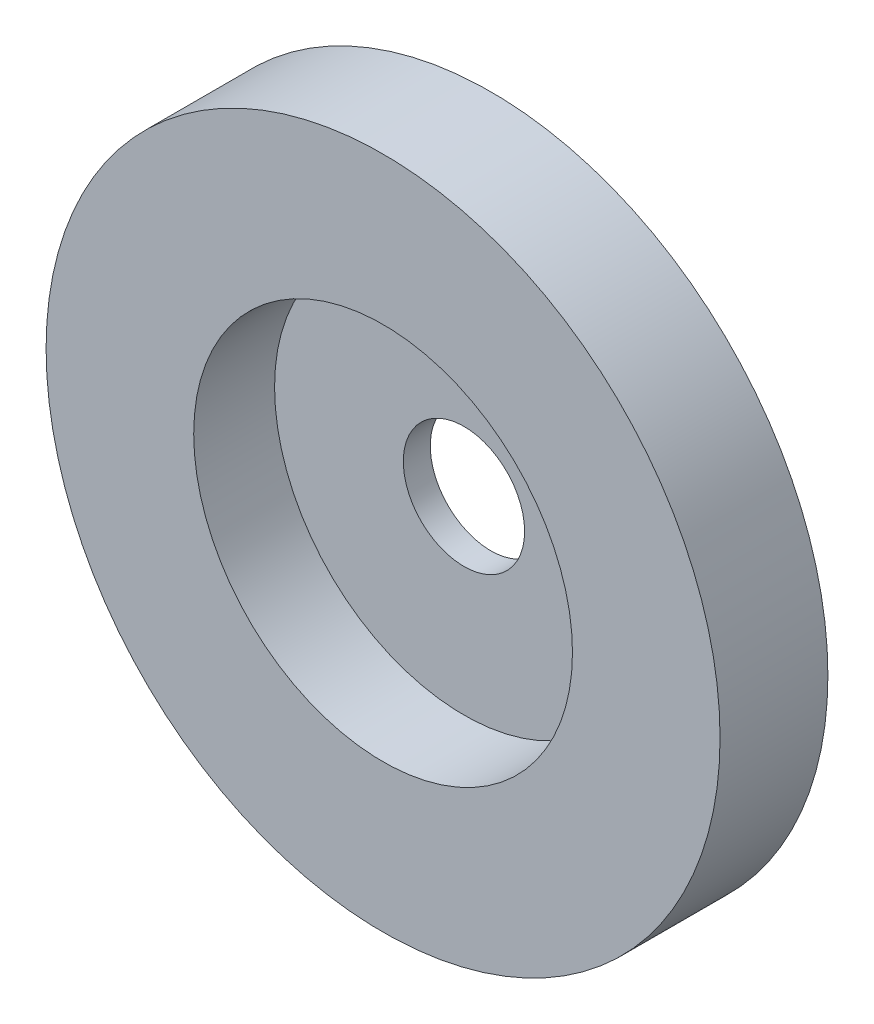
SolidWorks part; units mm, degrees
ref_plane "前基準面" through (0, 0, 0) normal (0, 0, 1) x (1, 0, 0)
ref_plane "上基準面" through (0, 0, 0) normal (0, 1, 0) x (1, 0, 0)
ref_plane "右基準面" through (0, 0, 0) normal (1, 0, 0) x (0, 0, -1)
sketch "草圖1" plane through (0, 0, 0) normal (0, 0, 1) x (1, 0, 0)
  circle A0 centre (0, 0) radius 25
extrude "填料-伸長1" add sketch "草圖1" along normal blind 8 contours A0
sketch "草圖2" plane through (0, 0, 0) normal (0, 0, 1) x (1, 0, 0)
  circle A0 centre (0, 0) radius 4.5
sketch "草圖7" plane through (0, 0, 8) normal (0, 0, 1) x (1, 0, 0)
  circle A0 centre (0, 0) radius 14.05
extrude "除料-伸長6" cut sketch "草圖7" against normal blind 6
extrude "除料-伸長7" cut sketch "草圖2" along normal blind 11.5
